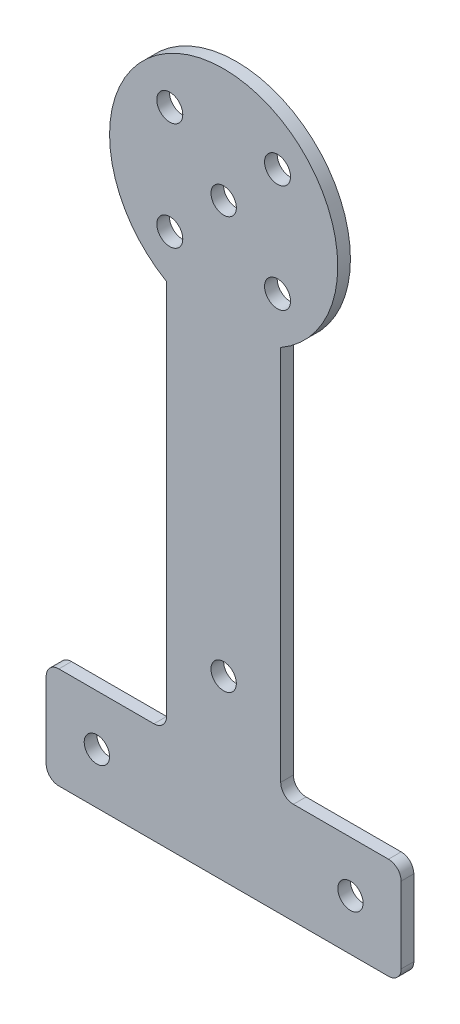
SolidWorks part; units mm, degrees
ref_plane "前视基准面" through (0, 0, 0) normal (0, 0, 1) x (1, 0, 0)
ref_plane "上视基准面" through (0, 0, 0) normal (0, 1, 0) x (1, 0, 0)
ref_plane "右视基准面" through (0, 0, 0) normal (1, 0, 0) x (0, 0, -1)
sketch "草图1" plane through (0, 0, 0) normal (0, 0, 1) x (1, 0, 0)
  line L2 (-13.3404, 27.5655) -> (-13.3404, 112.5655) construction
  line L3 (-13.3404, 112.5655) -> (-7.3404, 112.5655) construction
  line L6 (14.6596, 19.5655) -> (14.6596, 35.5655)
  line L9 (-41.3404, 19.5655) -> (-41.3404, 35.5655)
  line L11 (-41.3404, 35.5655) -> (-22.3404, 35.5655)
  line L14 (-33.3404, 27.5655) -> (-13.3404, 27.5655) construction
  line L15 (-13.3404, 27.5655) -> (6.6596, 27.5655) construction
  line L16 (-4.3404, 35.5655) -> (14.6596, 35.5655)
  line L17 (-41.3404, 19.5655) -> (14.6596, 19.5655)
  line L18 (-13.3404, 112.5655) -> (-13.3404, 121.0655) construction
  line L19 (-13.3404, 121.0655) -> (-4.8404, 121.0655) construction
  line L20 (-4.3404, 35.5655) -> (-4.3404, 96.9771)
  line L21 (-22.3404, 35.5655) -> (-22.3404, 96.9771)
  circle A4 centre (-33.3404, 27.5655) radius 2
  circle A5 centre (6.6596, 27.5655) radius 2
  circle A9 centre (-13.3404, 112.5655) radius 2
  circle A12 centre (-13.3404, 47.5655) radius 2
  circle A13 centre (-4.8404, 121.0655) radius 2.05
  circle A14 centre (-4.8404, 104.0655) radius 2.05
  circle A15 centre (-21.8404, 104.0655) radius 2.05
  circle A16 centre (-21.8404, 121.0655) radius 2.05
  circle A17 centre (-13.3404, 112.5655) radius 18 construction
  arc A18 (-22.3404, 96.9771) -> (-4.3404, 96.9771) centre (-13.3404, 112.5655) cw
  dimension "D5" = 4
  dimension "D7" = 4
  dimension "D8" = 65
  dimension "D2" = 20
  dimension "D3" = 8
  dimension "D4" = 8
  dimension "D9" = 8
  dimension "D10" = 20
  dimension "D11" = 20
  dimension "D12" = 8
extrude "凸台-拉伸1" add sketch "草图1" along normal blind 2
fillet "圆角1" radius 2 6 edges at (14.6596, 35.5655, 1) (14.6596, 19.5655, 1) (-41.3404, 19.5655, 1) (-41.3404, 35.5655, 1) (-4.3404, 35.5655, 1) (-22.3404, 35.5655, 1)
